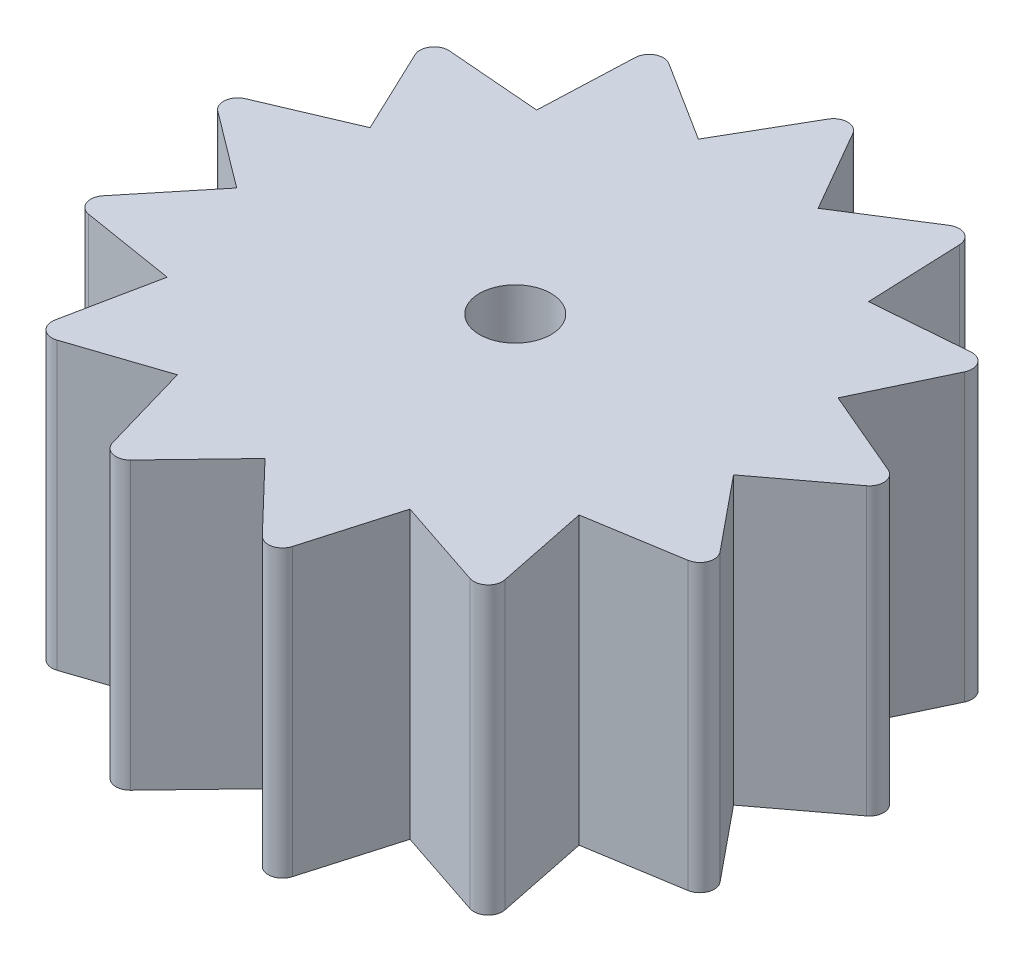
SolidWorks part; units mm, degrees
ref_plane "Front" through (0, 0, 0) normal (0, 0, 1) x (1, 0, 0)
ref_plane "Top" through (0, 0, 0) normal (0, 1, 0) x (1, 0, 0)
ref_plane "Right" through (0, 0, 0) normal (1, 0, 0) x (0, 0, -1)
sketch "Sketch1" plane through (0, 0, 0) normal (0, 1, 0) x (1, 0, 0)
  line L0 (2.3209, 2.6198) -> (3.9907, 2.7546)
  line L1 (3.9907, 2.7546) -> (3.2726, 1.2411)
  line L2 (3.2726, 1.2411) -> (4.8137, 0.5845)
  line L3 (4.8137, 0.5845) -> (3.4745, -0.4219)
  line L4 (3.4745, -0.4219) -> (4.534, -1.7195)
  line L5 (4.534, -1.7195) -> (2.8804, -1.9882)
  line L6 (2.8804, -1.9882) -> (3.2155, -3.6296)
  line L7 (3.2155, -3.6296) -> (1.6265, -3.0991)
  line L8 (1.6265, -3.0991) -> (1.1605, -4.7082)
  line L9 (1.1605, -4.7082) -> (0, -3.5)
  line L10 (0, -3.5) -> (-1.1605, -4.7082)
  line L11 (-1.1605, -4.7082) -> (-1.6265, -3.0991)
  line L12 (-1.6265, -3.0991) -> (-3.2155, -3.6296)
  line L13 (-3.2155, -3.6296) -> (-2.8804, -1.9882)
  line L14 (-2.8804, -1.9882) -> (-4.534, -1.7195)
  line L15 (-4.534, -1.7195) -> (-3.4745, -0.4219)
  line L16 (-3.4745, -0.4219) -> (-4.8137, 0.5845)
  line L17 (-4.8137, 0.5845) -> (-3.2726, 1.2411)
  line L18 (-3.2726, 1.2411) -> (-3.9907, 2.7546)
  line L19 (-3.9907, 2.7546) -> (-2.3209, 2.6198)
  line L20 (-2.3209, 2.6198) -> (-2.2535, 4.2936)
  line L21 (-2.2535, 4.2936) -> (-0.8376, 3.3983)
  line L22 (-0.8376, 3.3983) -> (0, 4.8491)
  line L23 (0, 4.8491) -> (0.8376, 3.3983)
  line L24 (0.8376, 3.3983) -> (2.2535, 4.2936)
  line L25 (2.2535, 4.2936) -> (2.3209, 2.6198)
  line L26 (-0.8376, 3.3983) -> (0.8376, 3.3983) construction
  circle A0 centre (0, 0) radius 3.5 construction
  circle A1 centre (0, 0) radius 0.5
  point P44 (0, 0)
  dimension "D2" = 7
  dimension "D4" = 1
  dimension "D3" = 60
  dimension "D5" = 1.6752
  dimension "D6" = 1.4508
  dimension "D1" = 13
extrude "Boss-Extrude1" add sketch "Sketch1" along normal blind 4
sketch "Sketch2" plane through (0, 0, 0) normal (0, -1, 0) x (1, 0, 0)
  line L168 (-2.3565, -0.3552) -> (-2.394, -0.7385)
  line L169 (-2.5053, 0) -> (-2.3565, -0.3552)
  line L170 (-2.3565, 0.3552) -> (-2.5053, 0)
  line L171 (-2.394, 0.7385) -> (-2.3565, 0.3552)
  line L172 (-2.1471, 1.034) -> (-2.394, 0.7385)
  line L173 (-2.07, 1.4113) -> (-2.1471, 1.034)
  line L174 (-1.747, 1.6209) -> (-2.07, 1.4113)
  line L175 (-1.562, 1.9587) -> (-1.747, 1.6209)
  line L176 (-1.1916, 2.0639) -> (-1.562, 1.9587)
  line L177 (-0.9153, 2.3321) -> (-1.1916, 2.0639)
  line L178 (-0.5303, 2.3234) -> (-0.9153, 2.3321)
  line L179 (-0.1872, 2.4983) -> (-0.5303, 2.3234)
  line L180 (0.1781, 2.3765) -> (-0.1872, 2.4983)
  line L181 (0.5575, 2.4425) -> (0.1781, 2.3765)
  line L182 (0.8707, 2.2184) -> (0.5575, 2.4425)
  line L183 (1.2527, 2.1697) -> (0.8707, 2.2184)
  line L184 (1.4859, 1.8632) -> (1.2527, 2.1697)
  line L185 (1.8365, 1.704) -> (1.4859, 1.8632)
  line L186 (1.969, 1.3425) -> (1.8365, 1.704)
  line L187 (2.2572, 1.087) -> (1.969, 1.3425)
  line L188 (2.2773, 0.7024) -> (2.2572, 1.087)
  line L189 (2.4773, 0.3734) -> (2.2773, 0.7024)
  line L190 (2.3831, 0) -> (2.4773, 0.3734)
  line L191 (2.4773, -0.3734) -> (2.3831, 0)
  line L192 (2.2773, -0.7024) -> (2.4773, -0.3734)
  line L193 (2.2572, -1.087) -> (2.2773, -0.7024)
  line L194 (1.969, -1.3425) -> (2.2572, -1.087)
  line L195 (1.8365, -1.704) -> (1.969, -1.3425)
  line L196 (1.4859, -1.8632) -> (1.8365, -1.704)
  line L197 (1.2527, -2.1697) -> (1.4859, -1.8632)
  line L198 (0.8707, -2.2184) -> (1.2527, -2.1697)
  line L199 (0.5575, -2.4425) -> (0.8707, -2.2184)
  line L200 (0.1781, -2.3765) -> (0.5575, -2.4425)
  line L201 (-0.1872, -2.4983) -> (0.1781, -2.3765)
  line L202 (-0.5303, -2.3234) -> (-0.1872, -2.4983)
  line L203 (-0.9153, -2.3321) -> (-0.5303, -2.3234)
  line L204 (-1.1916, -2.0639) -> (-0.9153, -2.3321)
  line L205 (-1.562, -1.9587) -> (-1.1916, -2.0639)
  line L206 (-1.747, -1.6209) -> (-1.562, -1.9587)
  line L207 (-2.07, -1.4113) -> (-1.747, -1.6209)
  line L208 (-2.1471, -1.034) -> (-2.07, -1.4113)
  line L209 (-2.394, -0.7385) -> (-2.1471, -1.034)
  line L210 (-2.3565, -0.3552) -> (-2.394, -0.7385)
  line L211 (-2.5053, 0) -> (-2.3565, -0.3552)
  line L212 (-2.3565, 0.3552) -> (-2.5053, 0)
  line L213 (-2.394, 0.7385) -> (-2.3565, 0.3552)
  line L214 (-2.1471, 1.034) -> (-2.394, 0.7385)
  line L215 (-2.07, 1.4113) -> (-2.1471, 1.034)
  line L216 (-1.747, 1.6209) -> (-2.07, 1.4113)
  line L217 (-1.562, 1.9587) -> (-1.747, 1.6209)
  line L218 (-1.1916, 2.0639) -> (-1.562, 1.9587)
  line L219 (-0.9153, 2.3321) -> (-1.1916, 2.0639)
  line L220 (-0.5303, 2.3234) -> (-0.9153, 2.3321)
  line L221 (-0.1872, 2.4983) -> (-0.5303, 2.3234)
  line L222 (0.1781, 2.3765) -> (-0.1872, 2.4983)
  line L223 (0.5575, 2.4425) -> (0.1781, 2.3765)
  line L224 (0.8707, 2.2184) -> (0.5575, 2.4425)
  line L225 (1.2527, 2.1697) -> (0.8707, 2.2184)
  line L226 (1.4859, 1.8632) -> (1.2527, 2.1697)
  line L227 (1.8365, 1.704) -> (1.4859, 1.8632)
  line L228 (1.969, 1.3425) -> (1.8365, 1.704)
  line L229 (2.2572, 1.087) -> (1.969, 1.3425)
  line L230 (2.2773, 0.7024) -> (2.2572, 1.087)
  line L231 (2.4773, 0.3734) -> (2.2773, 0.7024)
  line L232 (2.3831, 0) -> (2.4773, 0.3734)
  line L233 (2.4773, -0.3734) -> (2.3831, 0)
  line L234 (2.2773, -0.7024) -> (2.4773, -0.3734)
  line L235 (2.2572, -1.087) -> (2.2773, -0.7024)
  line L236 (1.969, -1.3425) -> (2.2572, -1.087)
  line L237 (1.8365, -1.704) -> (1.969, -1.3425)
  line L238 (1.4859, -1.8632) -> (1.8365, -1.704)
  line L239 (1.2527, -2.1697) -> (1.4859, -1.8632)
  line L240 (0.8707, -2.2184) -> (1.2527, -2.1697)
  line L241 (0.5575, -2.4425) -> (0.8707, -2.2184)
  line L242 (0.1781, -2.3765) -> (0.5575, -2.4425)
  line L243 (-0.1872, -2.4983) -> (0.1781, -2.3765)
  line L244 (-0.5303, -2.3234) -> (-0.1872, -2.4983)
  line L245 (-0.9153, -2.3321) -> (-0.5303, -2.3234)
  line L246 (-1.1916, -2.0639) -> (-0.9153, -2.3321)
  line L247 (-1.562, -1.9587) -> (-1.1916, -2.0639)
  line L248 (-1.747, -1.6209) -> (-1.562, -1.9587)
  line L249 (-2.07, -1.4113) -> (-1.747, -1.6209)
  line L250 (-2.1471, -1.034) -> (-2.07, -1.4113)
  line L251 (-2.394, -0.7385) -> (-2.1471, -1.034)
  dimension "D1" = 0.1
extrude "Cut-Extrude1" cut sketch "Sketch2" against normal blind 3
fillet "Fillet1" radius 0.2 13 edges at (-4.8137, 2, -0.5845) (-4.534, 2, 1.7195) (-3.2155, 2, 3.6296) (-1.1605, 2, 4.7082) (1.1605, 2, 4.7082) (3.2155, 2, 3.6296) (4.534, 2, 1.7195) (4.8137, 2, -0.5845) (3.9907, 2, -2.7546) (2.2535, 2, -4.2936) (0, 2, -4.8491) (-2.2535, 2, -4.2936) (-3.9907, 2, -2.7546)
